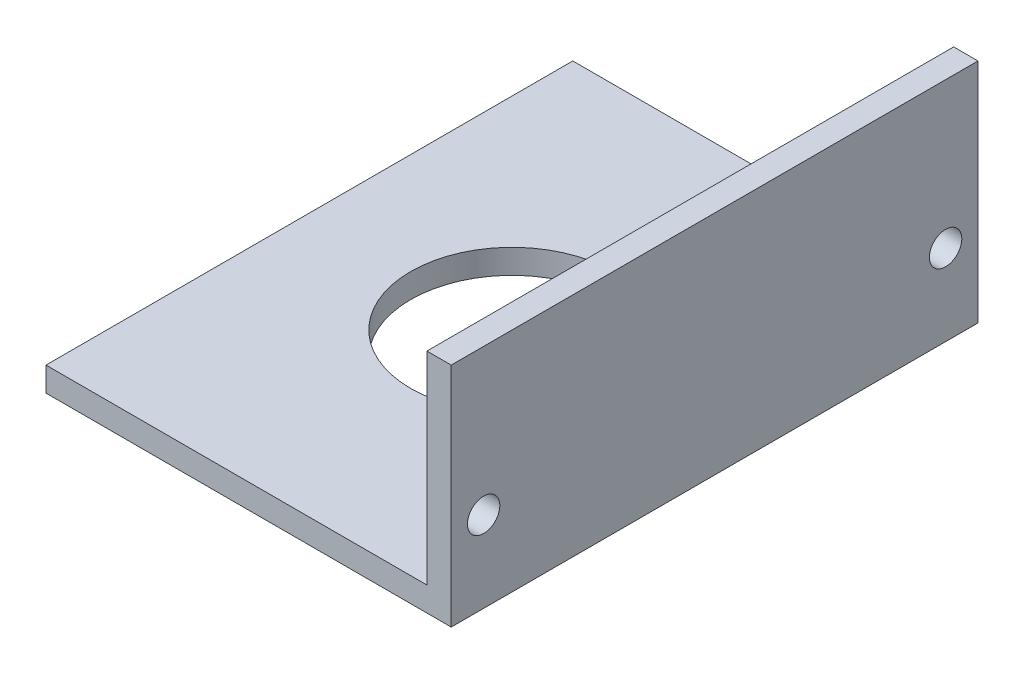
SolidWorks part; units mm, degrees
ref_plane "Front Plane" through (0, 0, 0) normal (0, 0, 1) x (1, 0, 0)
ref_plane "Top Plane" through (0, 0, 0) normal (0, 1, 0) x (1, 0, 0)
ref_plane "Right Plane" through (0, 0, 0) normal (1, 0, 0) x (0, 0, -1)
sketch "Sketch1" plane through (0, 0, 0) normal (0, 1, 0) x (1, 0, 0)
  line L1 (-25, 32.5) -> (25, 32.5)
  line L2 (-25, 32.5) -> (-25, -32.5)
  line L3 (-25, -32.5) -> (25, -32.5)
  line L4 (25, 32.5) -> (25, -32.5)
  line L5 (-25, 32.5) -> (25, -32.5) construction
  line L6 (-25, -32.5) -> (25, 32.5) construction
  point P0 (0, 0)
extrude "Boss-Extrude1" add sketch "Sketch1" along normal blind 3
sketch "Sketch2" plane through (0, 3, 0) normal (0, 1, 0) x (1, 0, 0)
  line L0 (22, -32.5) -> (22, 32.5)
  line L1 (-25, -32.5) -> (25, -32.5) construction
  line L2 (25, 32.5) -> (-25, 32.5) construction
  line L8 (25, -32.5) -> (25, 32.5)
  line L9 (25, 32.5) -> (-25, 32.5)
  line L10 (-25, 32.5) -> (-25, -32.5)
  line L11 (-25, -32.5) -> (25, -32.5)
  line L12 (25, -32.5) -> (25, 32.5)
  line L13 (25, 32.5) -> (22, 32.5)
  line L15 (22, -32.5) -> (25, -32.5)
  dimension "D1" = 0
extrude "Boss-Extrude2" add sketch "Sketch2" along normal blind 25
sketch "Sketch4" plane through (0, 0, 0) normal (0, -1, 0) x (1, 0, 0)
  circle A0 centre (0, 0) radius 12.4992
extrude "Cut-Extrude1" cut sketch "Sketch4" against normal up to surface (3 mm away) up to face at (-1.5, 3, 0)
sketch "Sketch5" plane through (22, 0, 0) normal (-1, 0, 0) x (0, 0, 1)
  line L0 (32.5, 28) -> (32.5, 3) construction
  line L1 (-32.5, 28) -> (-32.5, 3) construction
  line L2 (-32.5, 3) -> (32.5, 3) construction
  circle A0 centre (28.5, 10) radius 2
  circle A1 centre (-28.5, 10) radius 2
  dimension "D1" = 4
  dimension "D2" = 4
  dimension "D3" = 7
  dimension "D4" = 7
extrude "Cut-Extrude2" cut sketch "Sketch5" against normal blind 30
